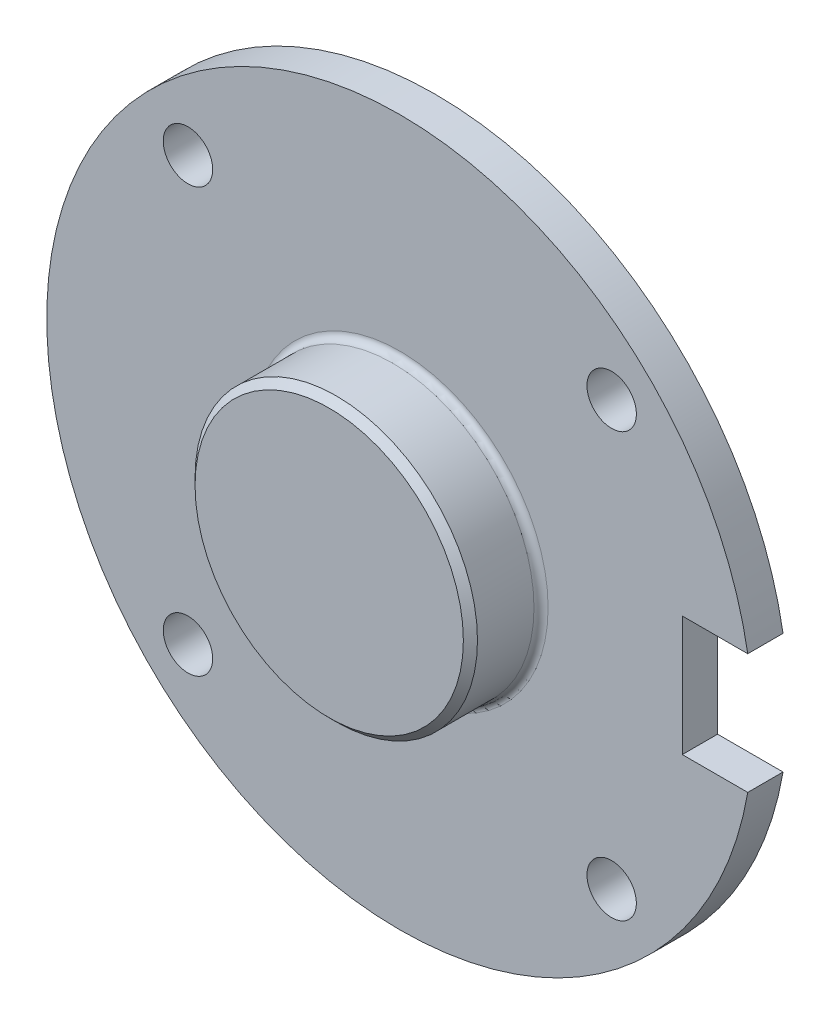
SolidWorks part; units mm, degrees
ref_plane "Front Plane" through (0, 0, 0) normal (0, 0, 1) x (1, 0, 0)
ref_plane "Top Plane" through (0, 0, 0) normal (0, 1, 0) x (1, 0, 0)
ref_plane "Right Plane" through (0, 0, 0) normal (1, 0, 0) x (0, 0, -1)
other "Configuration Table"
sketch "Sketch1" plane through (0, 0, 0) normal (1, 0, 0) x (0, 0, -1)
  line L0 (0, 0) -> (-15, 0)
  line L1 (-15, 0) -> (-15, 19)
  line L2 (-14, 20) -> (-6, 20)
  line L3 (-15, 19) -> (-14, 20)
  line L5 (-5, 21) -> (-5, 50)
  line L6 (-5, 50) -> (0, 50)
  line L7 (0, 50) -> (0, 0)
  line L8 (-50, 0) -> (20, 0) construction
  arc A0 (-6, 20) -> (-5, 21) centre (-6, 21) ccw
  point P3 (-15, 20)
  dimension "D9" = 1
  dimension "D1" = 15
  dimension "D2" = 5
  dimension "D3" = 20
  dimension "D6" = 50
revolve "Revolve1" add sketch "Sketch1" angle 360 about L8
sketch "Sketch5" plane through (0, 0, 5) normal (0, 0, 1) x (1, 0, 0)
  line L1 (40, -8.5) -> (50, -8.5)
  line L2 (40, -8.5) -> (40, 8.5)
  line L3 (40, 8.5) -> (50, 8.5)
  line L4 (50, -8.5) -> (50, 8.5)
  circle A0 centre (0, 0) radius 50 construction
  point P4 (40, 0)
  dimension "D1" = 17
  dimension "D2" = 10
extrude "Extrude2" cut sketch "Sketch5" against normal through all
hole_wizard "Ø7.0 (7) Diameter Hole1" positions "Sketch7" profile "Sketch6" hole size "Ø7.0" standard "Ansi Metric"
sketch "Sketch7" plane through (0, 0, 5) normal (0, 0, 1) x (1, 0, 0)
  point P0 (-30, 30)
  dimension "D1" = 30
  dimension "D2" = 30
sketch "Sketch6" plane through (-30, 30, 5) normal (1, 0, 0) x (0, -1, 0)
  line L0 (0, 0) -> (0, 12.103)
  line L1 (0, 12.103) -> (3.5, 10)
  line L2 (3.5, 10) -> (3.5, 0)
  line L5 (3.5, 0) -> (0, 0)
  line L10 (0, 12.103) -> (-3.5, 10) construction
  line L11 (0, -6.35) -> (0, 107.95) construction
  dimension "Hole Dia." = 7
  dimension "Hole Depth" = 10
  dimension "Drill Angle" = 118
pattern_circular "CirPattern1" count 4 over 360 about axis through (0, 0, 0) along (0, 0, 1) of "Ø7.0 (7) Diameter Hole1"
